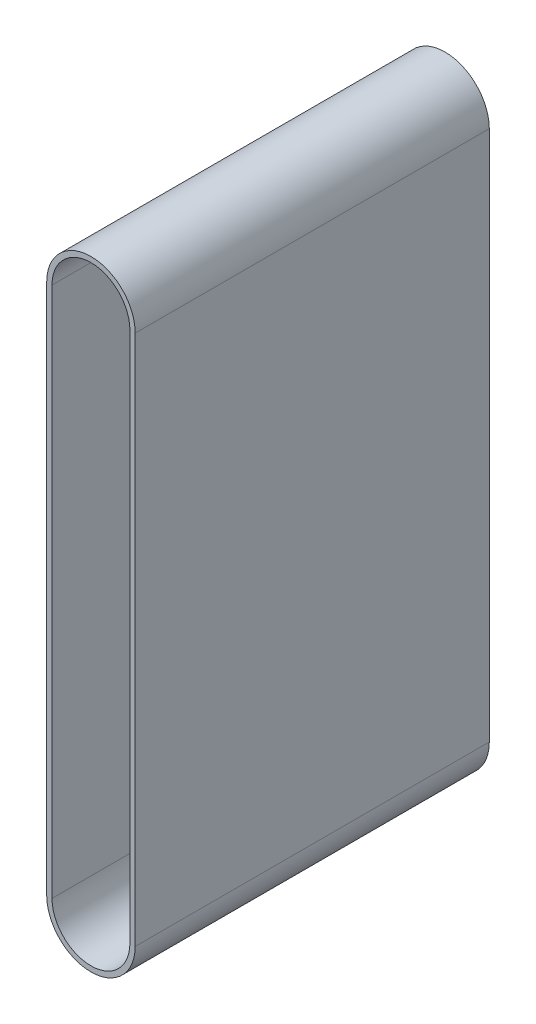
SolidWorks part; units mm, degrees
ref_plane "Plan de face" through (0, 0, 0) normal (0, 0, 1) x (1, 0, 0)
ref_plane "Plan de dessus" through (0, 0, 0) normal (0, 1, 0) x (1, 0, 0)
ref_plane "Plan de droite" through (0, 0, 0) normal (1, 0, 0) x (0, 0, -1)
sketch "Esquisse1" plane through (0, 0, 0) normal (0, 0, 1) x (1, 0, 0)
  line L0 (0, 0) -> (0, 300) construction
  line L1 (-25, 0) -> (-25, 300)
  line L2 (25, 0) -> (25, 300)
  arc A0 (-25, 0) -> (25, 0) centre (0, 0) ccw
  arc A1 (25, 300) -> (-25, 300) centre (0, 300) ccw
  point P3 (0, 150)
  dimension "D1" = 50
extrude "Boss.-Extru.1" add sketch "Esquisse1" along normal blind 200
sketch "Esquisse2" plane through (0, 0, 200) normal (0, 0, 1) x (1, 0, 0)
  line L0 (0, 300) -> (0, 0) construction
  line L1 (22, 300) -> (22, 0)
  line L2 (-22, 300) -> (-22, 0)
  line L3 (-25, 300) -> (-25, 0) construction
  arc A0 (22, 300) -> (-22, 300) centre (0, 300) ccw
  arc A1 (-22, 0) -> (22, 0) centre (0, 0) ccw
  point P4 (0, 150)
  dimension "D1" = 3
extrude "Enlèv. mat.-Extru.1" cut sketch "Esquisse2" against normal blind 200
